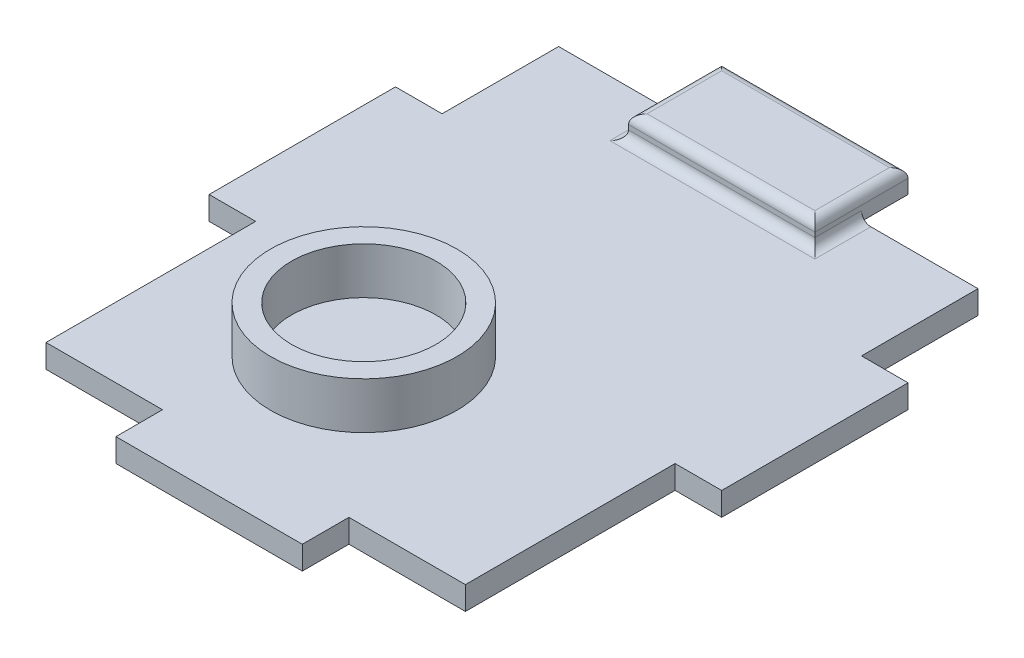
SolidWorks part; units mm, degrees
ref_plane "Front Plane" through (0, 0, 0) normal (0, 0, 1) x (1, 0, 0)
ref_plane "Top Plane" through (0, 0, 0) normal (0, 1, 0) x (1, 0, 0)
ref_plane "Right Plane" through (0, 0, 0) normal (1, 0, 0) x (0, 0, -1)
sketch "Sketch1" plane through (0, 0, 0) normal (0, 1, 0) x (1, 0, 0)
  line L1 (0, 0) -> (90, 0)
  line L2 (0, 0) -> (0, 110)
  line L3 (0, 110) -> (90, 110)
  line L4 (90, 0) -> (90, 110)
  line L5 (0, 85) -> (-10, 85)
  line L6 (0, 85) -> (0, 45)
  line L7 (0, 45) -> (-10, 45)
  line L8 (-10, 85) -> (-10, 45)
  line L9 (25, 110) -> (65, 110)
  line L13 (90, 85) -> (100, 85)
  line L14 (90, 85) -> (90, 45)
  line L15 (90, 45) -> (100, 45)
  line L16 (100, 85) -> (100, 45)
  line L17 (65, 0) -> (25, 0)
  line L18 (65, 0) -> (65, -10)
  line L19 (65, -10) -> (25, -10)
  line L20 (25, 0) -> (25, -10)
  point P23 (45, 0)
  point P24 (45, 110)
  dimension "D1" = 90
  dimension "D2" = 110
  dimension "D3" = 10
  dimension "D5" = 10
  dimension "D6" = 10
  dimension "D8" = 40
  dimension "D9" = 40
  dimension "D10" = 40
  dimension "D11" = 45
  dimension "D12" = 45
extrude "Boss-Extrude1" add sketch "Sketch1" along normal blind 5 contours L1 L4 L3 L2 | L5 L8 L7 L2 | L16 L13 L4 L15 | L1 L20 L19 L18
sketch "Sketch4" plane through (0, 5, 0) normal (0, 1, 0) x (1, 0, 0)
  line L0 (0, 0) -> (0, 45) construction
  line L1 (65, 0) -> (90, 0) construction
  circle A0 centre (36.72, 31.47) radius 31.25
  circle A1 centre (36.72, 31.47) radius 15.5
  circle A2 centre (36.72, 31.47) radius 20
  dimension "D3" = 62.5
  dimension "D4" = 31
  dimension "D5" = 40
  dimension "D1" = 36.72
  dimension "D2" = 31.47
extrude "Boss-Extrude2" add sketch "Sketch4" along normal blind 10 contours A2 A1
sketch "Sketch5" plane through (0, 5, 0) normal (0, 1, 0) x (1, 0, 0)
  line L0 (0, 110) -> (90, 110) construction
  line L1 (65, 120) -> (25, 120)
  line L2 (65, 120) -> (65, 100)
  line L3 (65, 100) -> (25, 100)
  line L4 (25, 120) -> (25, 100)
  line L5 (65, 120) -> (25, 100) construction
  line L6 (65, 100) -> (25, 120) construction
  point P0 (45, 110)
  dimension "D1" = 20
  dimension "D2" = 40
extrude "Boss-Extrude3" add sketch "Sketch5" along normal blind 5
fillet "Fillet1" radius 2 7 edges at (25, 5, -105) (45, 5, -100) (65, 5, -105) (25, 10, -110) (45, 10, -100) (65, 10, -110) (45, 10, -120)
equation "\"D4@Sketch4\"=15.5*2"
